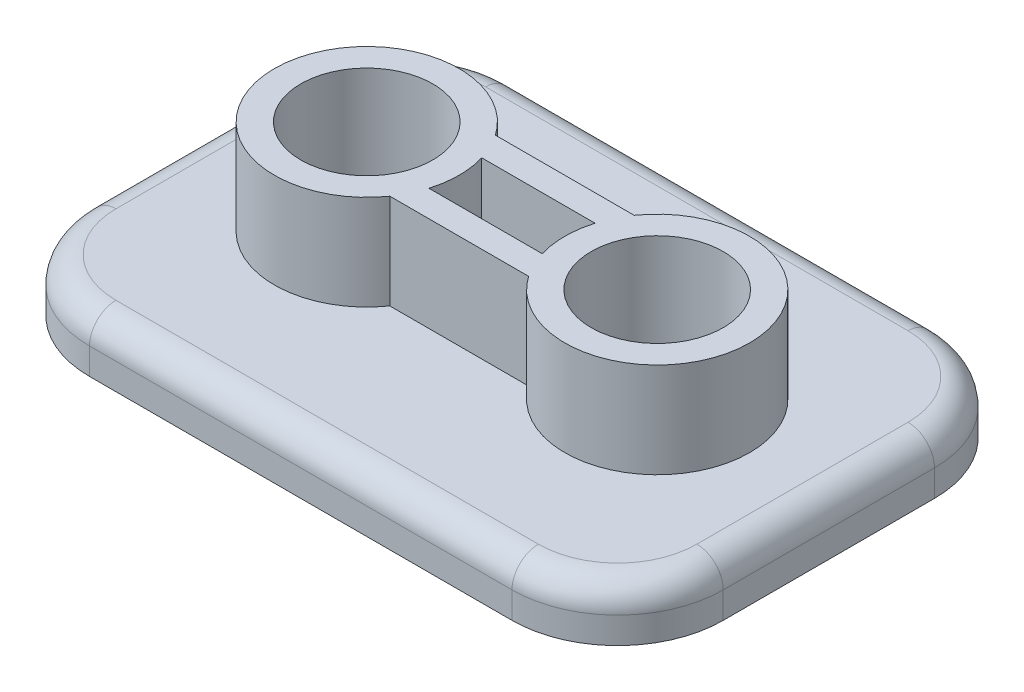
SolidWorks part; units mm, degrees
material "AISI 304"
ref_plane "정면" through (0, 0, 0) normal (0, 0, 1) x (1, 0, 0)
ref_plane "윗면" through (0, 0, 0) normal (0, 1, 0) x (1, 0, 0)
ref_plane "우측면" through (0, 0, 0) normal (1, 0, 0) x (0, 0, -1)
sketch "Sketch1" plane through (0, 0, 0) normal (0, 1, 0) x (1, 0, 0)
  line L1 (0, 0) -> (120, 0)
  line L2 (0, 0) -> (0, 80)
  line L3 (0, 80) -> (120, 80)
  line L4 (120, 0) -> (120, 80)
  dimension "D1" = 80
  dimension "D2" = 120
extrude "Boss-Extrude1" add sketch "Sketch1" along normal blind 10
sketch "Sketch2" plane through (0, 10, 0) normal (0, 1, 0) x (1, 0, 0)
  line L0 (60, 80) -> (60, 0) construction
  line L1 (120, 80) -> (0, 80) construction
  line L2 (0, 0) -> (120, 0) construction
  line L3 (0, 40) -> (120, 40) construction
  line L4 (0, 80) -> (0, 0) construction
  line L5 (120, 0) -> (120, 80) construction
  line L6 (70.7295, 35) -> (49.2705, 35)
  line L8 (49.2705, 45) -> (70.7295, 45)
  line L10 (73.1386, 50) -> (46.8614, 50)
  line L12 (73.1386, 30) -> (46.8614, 30)
  circle A0 centre (32.5, 40) radius 17.5
  circle A1 centre (32.5, 40) radius 12.5
  circle A2 centre (87.5, 40) radius 12.5
  circle A3 centre (87.5, 40) radius 17.5
  point P26 (60, 45)
  point P27 (60, 35)
  dimension "D3" = 25
  dimension "D4" = 35
  dimension "D1" = 10
  dimension "D2" = 20
  dimension "D5" = 55
extrude "Boss-Extrude2" add sketch "Sketch2" along normal blind 18 contours L8 A3 L10 A0 | A0 A1 | L12 A3 L6 A0 | A3 A2
fillet "Fillet1" radius 20 4 edges at (0, 5, -80) (120, 5, -80) (120, 5, 0) (0, 5, 0)
fillet "Fillet2" radius 5 8 edges at (5.8579, 10, -74.1421) (60, 10, -80) (114.1421, 10, -74.1421) (120, 10, -40) (114.1421, 10, -5.8579) (60, 10, 0) (5.8579, 10, -5.8579) (0, 10, -40)
